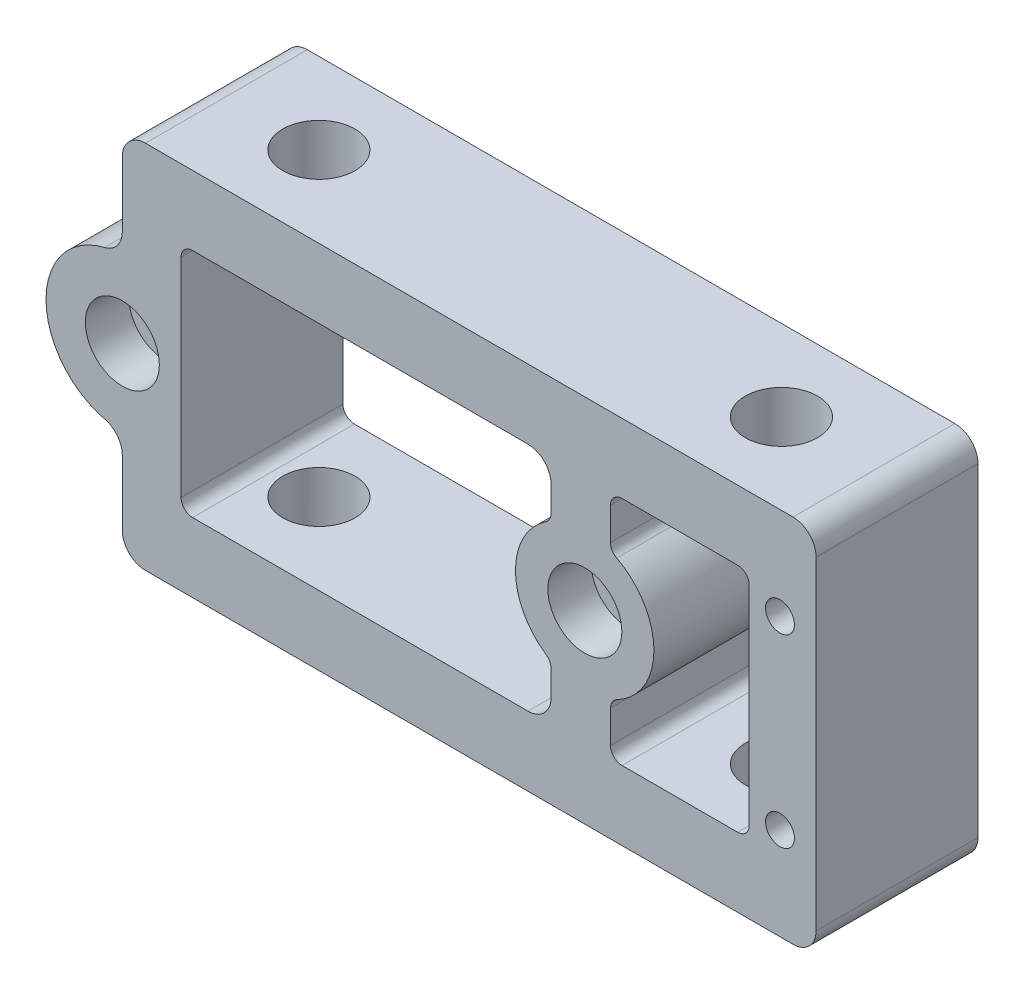
SolidWorks part; units mm, degrees
material "6061-T6 (SS)"
ref_plane "X-Y Datum" through (0, 0, 0) normal (0, 0, 1) x (1, 0, 0)
ref_plane "X-Z Datum" through (0, 0, 0) normal (0, 1, 0) x (1, 0, 0)
ref_plane "Y-Z Datum" through (0, 0, 0) normal (1, 0, 0) x (0, 0, -1)
other "Graphic1"
other "Graphic (Closed) -1"
other "Graphic2"
other "Graphic (Closed) -2"
other "Graphic3"
other "Graphic (Closed) -3"
sketch "Sketch1" plane through (0, 0, 0) normal (0, 0, 1) x (1, 0, 0)
  line L5 (-93.6625, 0) -> (0, 0) construction
  line L7 (-93.6625, -20.32) -> (-93.6625, 20.32)
  line L17 (-93.6625, -20.32) -> (0, -20.32)
  line L28 (-12.7, 15.2978) -> (-12.7, -16.3411) construction
  line L30 (-93.6625, 20.32) -> (0, 20.32)
  line L31 (0, 20.32) -> (0, -20.32)
  circle A4 centre (-84.9313, 0) radius 2.4892
  circle A7 centre (-34.1313, 0) radius 2.4892
  circle A8 centre (-12.7, 10.16) radius 1.5875
  circle A9 centre (-12.7, -10.16) radius 1.5875
  point P1 (-93.6625, 0)
  dimension "D2" = 93.6625
  dimension "D3" = 34.1313
  dimension "D5" = 3.175
  dimension "D1" = 8.7312
  dimension "D4" = 40.64
  dimension "D6" = 10.16
  dimension "D7" = 10.16
  dimension "D8" = 12.7
extrude "Boss-Extrude1" add sketch "Sketch1" against normal blind 17.78
sketch "Sketch3" plane through (0, 0, 0) normal (0, 0, 1) x (1, 0, 0)
  circle A2 centre (-84.9313, 0) radius 4.064
  circle A3 centre (-84.9313, 0) radius 2.4892 construction
  circle A4 centre (-34.1313, 0) radius 4.064
  dimension "D1" = 8.128
sketch "Sketch6" plane through (0, 20.32, 0) normal (0, 1, 0) x (1, 0, 0)
  line L0 (0, 17.78) -> (-93.6625, 17.78) construction
  line L1 (-72.2313, 8.89) -> (-21.4312, 8.89) construction
  circle A0 centre (-72.2313, 8.89) radius 3.9687
  circle A1 centre (-21.4312, 8.89) radius 3.9687
  point P4 (-46.8312, 17.78)
  point P5 (-46.8312, 8.89)
  dimension "D1" = 7.9375
  dimension "D2" = 8.89
  dimension "D3" = 50.8
extrude "Cut-Extrude4" cut sketch "Sketch6" against normal through all
sketch "Sketch5" plane through (0, 0, 0) normal (0, 0, 1) x (1, 0, 0)
  line L7 (-46.8312, 20.32) -> (-46.8313, -20.32) construction
  line L8 (0, 20.32) -> (-93.6625, 20.32) construction
  line L18 (-93.6625, -20.32) -> (0, -20.32) construction
  line B0 (-93.6625, -20.32) -> (-93.6625, 20.32)
  line B1 (-84.9312, -20.32) -> (-93.6625, -20.32)
  line B2 (-84.9313, -10.6225) -> (-84.9312, -20.32)
  line B3 (-84.9313, 10.6225) -> (-84.9312, 20.32)
  line B4 (-93.6625, 20.32) -> (-84.9312, 20.32)
  arc B5 (-84.9313, -10.6225) -> (-86.8806, -8.1522) centre (-87.4713, -10.6225) ccw
  arc B6 (-86.8806, 8.1522) -> (-86.8806, -8.1522) centre (-84.9313, 0) ccw
  arc B7 (-84.9313, 10.6225) -> (-86.8806, 8.1522) centre (-87.4713, 10.6225) cw
  line B8 (0, -20.32) -> (0, 20.32)
  line B9 (-8.7313, -20.32) -> (0, -20.32)
  line B10 (-8.7313, -10.6225) -> (-8.7313, -20.32)
  line B11 (-8.7312, 10.6225) -> (-8.7312, 20.32)
  line B12 (0, 20.32) -> (-8.7312, 20.32)
  arc B13 (-8.7313, -10.6225) -> (-6.7819, -8.1522) centre (-6.1912, -10.6225) cw
  arc B14 (-6.7819, 8.1522) -> (-6.7819, -8.1522) centre (-8.7312, 0) cw
  arc B15 (-8.7312, 10.6225) -> (-6.7819, 8.1522) centre (-6.1912, 10.6225) ccw
sketch_block_instance "Block1-1"
sketch_block "Block1"
sketch_block_instance "Block1-2"
extrude "Cut-Extrude3" cut sketch "Sketch5" against normal up to surface (17.78 mm away) up to face at (-11.1125, -10.16, -17.78)
fillet "Fillet1" radius 2.54 4 edges at (-84.9312, -20.32, -8.89) (-8.7313, -20.32, -8.89) (-8.7312, 20.32, -8.89) (-84.9312, 20.32, -8.89)
extrude "Cut-Extrude5" cut sketch "Sketch3" against normal blind 4.7752
ref_point "Point1"
ref_point "Point2"
sketch "Sketch7" plane through (0, 0, 0) normal (0, 0, 1) x (1, 0, 0)
  line L0 (-46.8312, 20.32) -> (-46.8313, -20.32) construction
  line L5 (-11.2713, 20.32) -> (-82.3912, 20.32) construction
  line L6 (-82.3912, -20.32) -> (-11.2713, -20.32) construction
  line L7 (-37.8425, 10.16) -> (-37.8425, 6.6551)
  line L8 (-60.7025, -12.7) -> (-40.3825, -12.7)
  line L9 (-63.2425, -10.16) -> (-63.2425, 10.16)
  line L10 (-60.7025, 12.7) -> (-40.3825, 12.7)
  line L14 (-37.8425, -10.16) -> (-37.8425, -6.6551)
  line L17 (-8.7313, -10.6225) -> (-8.7313, -17.78) construction
  line L18 (-8.7312, 10.6225) -> (-8.7313, -10.6225)
  line L19 (-8.7313, -10.6225) -> (0.3823, -10.6225)
  line L20 (0.3823, -10.6225) -> (0.3823, 10.6225)
  line L21 (0.3823, 10.6225) -> (-8.7312, 10.6225)
  arc A0 (-60.7025, -12.7) -> (-63.2425, -10.16) centre (-60.7025, -10.16) cw
  arc A1 (-40.3825, -12.7) -> (-37.8425, -10.16) centre (-40.3825, -10.16) ccw
  arc A2 (-40.3825, 12.7) -> (-37.8425, 10.16) centre (-40.3825, 10.16) cw
  arc A3 (-63.2425, 10.16) -> (-60.7025, 12.7) centre (-60.7025, 10.16) cw
  arc A5 (-37.8425, -6.6551) -> (-37.8425, 6.6551) centre (-34.1313, 0) cw
  point P0 (-46.8313, 0)
  point P1 (-41.7513, 0)
  point P2 (0, 0)
  point P3 (0, 0)
  point P25 (0, 0)
  point P26 (-63.2425, 0)
  point P27 (0, 0)
  point P29 (0, 0)
  point P35 (0, 0)
  point P39 (0, 0)
  dimension "D3" = 2.54
  dimension "D4" = 7.62
  dimension "D1" = 25.4
  dimension "D2" = 25.4
extrude "Cut-Extrude6" cut sketch "Sketch7" against normal through all
sketch "Sketch8" plane through (0, 0, 0) normal (0, 0, 1) x (1, 0, 0)
  line L2 (-78.4825, -12.7) -> (-78.4825, 12.7)
  line L5 (-82.3912, -20.32) -> (-11.2713, -20.32) construction
  line L9 (-31.3164, 12.7) -> (-16.0764, 12.7)
  line L10 (-16.0764, 12.7) -> (-16.0764, -12.7)
  line L11 (-16.0764, -12.7) -> (-31.3164, -12.7)
  line L15 (-31.3164, 7.0466) -> (-31.3164, 12.7)
  line L16 (-31.3164, -7.0466) -> (-31.3164, -12.7)
  line L17 (-8.7312, 17.78) -> (-8.7313, -17.78) construction
  line L18 (-78.4825, 12.7) -> (-60.7025, 12.7)
  line L19 (-60.7025, 12.7) -> (-60.7025, -12.7)
  line L20 (-60.7025, -12.7) -> (-78.4825, -12.7)
  arc A0 (-31.3164, 7.0466) -> (-31.3164, -7.0466) centre (-34.1313, 0) cw
  point P4 (-78.4825, 0)
  point P16 (-16.0764, 0)
  point P19 (-26.5433, 0)
  dimension "D4" = 7.588
  dimension "D1" = 17.78
  dimension "D2" = 20.32
  dimension "D5" = 15.24
  dimension "D6" = 25.4
  dimension "D7" = 20.32
  dimension "D8" = 7.3452
extrude "Cut-Extrude7" cut sketch "Sketch8" against normal up to surface (17.78 mm away) up to face at (-48.3934, 0, -17.78)
fillet "Fillet2" radius 1.27 10 edges at (-31.3164, -12.7, -8.89) (-16.0764, -12.7, -8.89) (-16.0764, 12.7, -8.89) (-31.3164, 12.7, -8.89) (-31.3164, 7.0466, -8.89) (-31.3164, -7.0466, -8.89) (-37.8425, -6.6551, -8.89) (-37.8425, 6.6551, -8.89) (-78.4825, -12.7, -8.89) (-78.4825, 12.7, -8.89)
